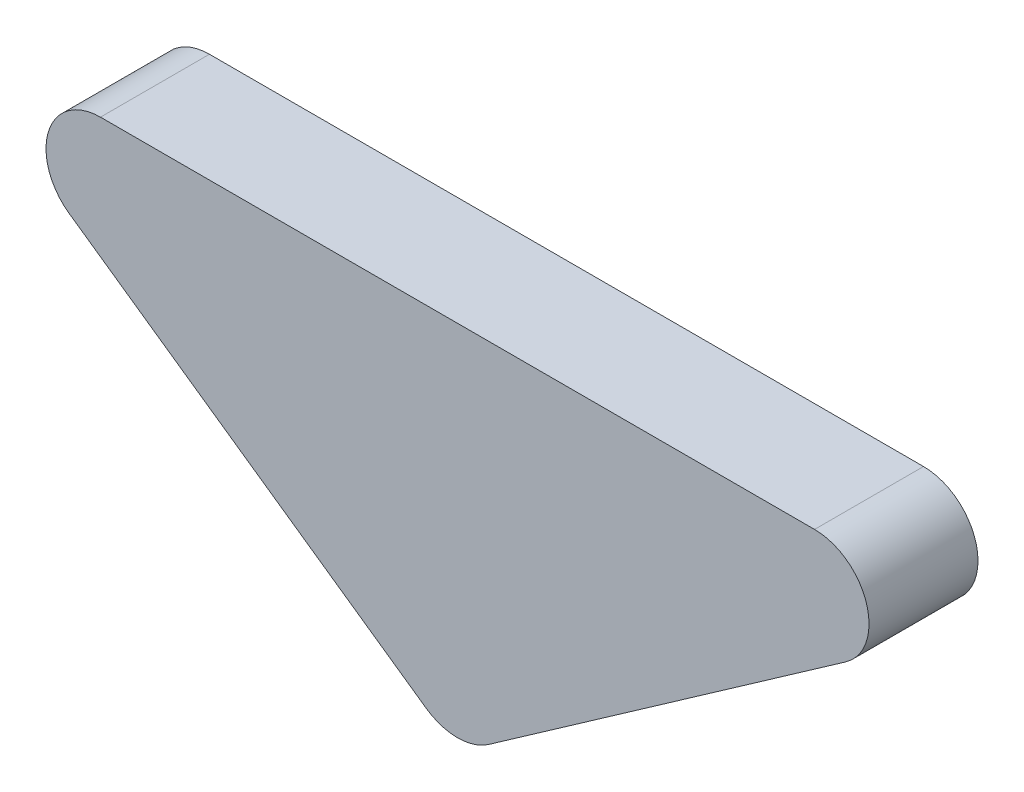
SolidWorks part; units mm, degrees
ref_plane "前视基准面" through (0, 0, 0) normal (0, 0, 1) x (1, 0, 0)
ref_plane "上视基准面" through (0, 0, 0) normal (0, 1, 0) x (1, 0, 0)
ref_plane "右视基准面" through (0, 0, 0) normal (1, 0, 0) x (0, 0, -1)
sketch "草图1" plane through (0, 0, 0) normal (0, 0, 1) x (1, 0, 0)
  line L0 (2.8679, -4.0958) -> (35.634, 18.8473)
  line L1 (-35.634, 18.8473) -> (-2.8679, -4.0958)
  line L2 (-32.7661, 27.9431) -> (32.7661, 27.9431)
  line L3 (0, 0) -> (-32.7661, 22.9431) construction
  line L4 (0, 0) -> (32.7661, 22.9431) construction
  arc A0 (-2.8679, -4.0958) -> (2.8679, -4.0958) centre (0, 0) ccw
  arc A1 (32.7661, 27.9431) -> (35.634, 18.8473) centre (32.7661, 22.9431) cw
  arc A2 (-32.7661, 27.9431) -> (-35.634, 18.8473) centre (-32.7661, 22.9431) ccw
  dimension "D3" = 5
  dimension "D5" = 5
  dimension "D6" = 5
  dimension "D1" = 40
  dimension "D2" = 40
  dimension "D4" = 110
extrude "凸台-拉伸1" add sketch "草图1" along normal blind 10
